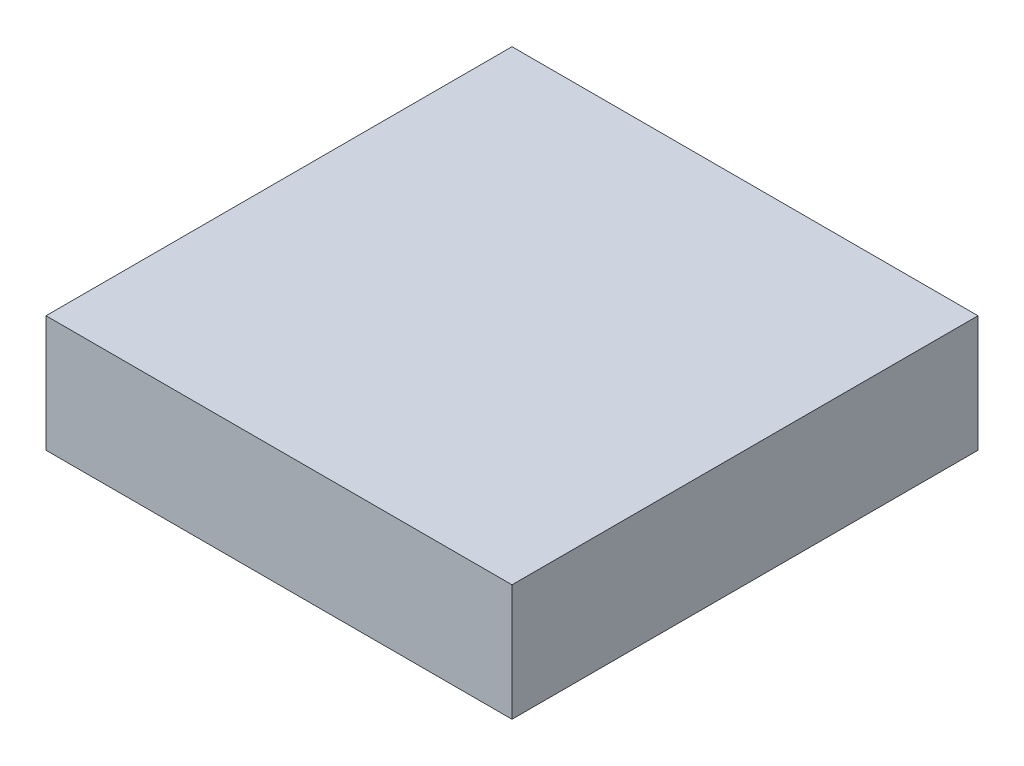
SolidWorks part; units mm, degrees
ref_plane "Front Plane" through (0, 0, 0) normal (0, 0, 1) x (1, 0, 0)
ref_plane "Top Plane" through (0, 0, 0) normal (0, 1, 0) x (1, 0, 0)
ref_plane "Right Plane" through (0, 0, 0) normal (1, 0, 0) x (0, 0, -1)
sketch "Sketch1" plane through (0, 0, 0) normal (0, 1, 0) x (1, 0, 0)
  line L1 (-0.886, 0.9835) -> (1.114, 0.9835)
  line L2 (-0.886, 0.9835) -> (-0.886, -1.0165)
  line L3 (-0.886, -1.0165) -> (1.114, -1.0165)
  line L4 (1.114, 0.9835) -> (1.114, -1.0165)
  dimension "D1" = 2
  dimension "D2" = 2
extrude "Boss-Extrude1" add sketch "Sketch1" along normal blind 0.5
